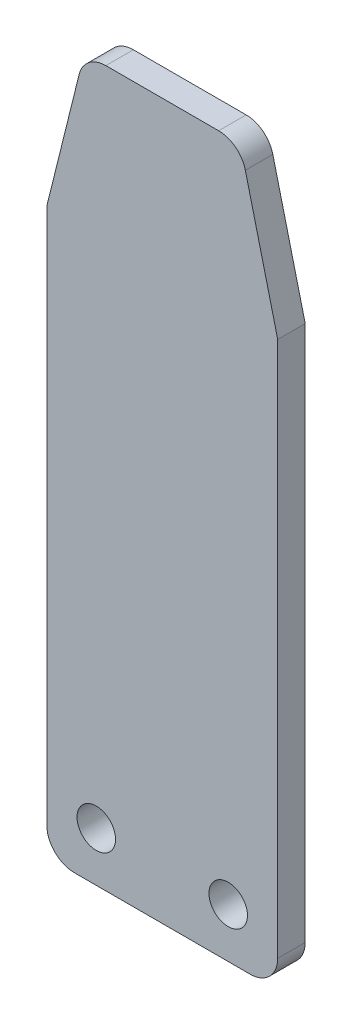
SolidWorks part; units mm, degrees
material "1.0116 (S235J2G3)"
ref_plane "Front Plane" through (0, 0, 0) normal (0, 0, 1) x (1, 0, 0)
ref_plane "Top Plane" through (0, 0, 0) normal (0, 1, 0) x (1, 0, 0)
ref_plane "Right Plane" through (0, 0, 0) normal (1, 0, 0) x (0, 0, -1)
sketch "Sketch1" plane through (0, 0, 0) normal (0, 0, 1) x (1, 0, 0)
  line L0 (-20.5177, 260) -> (20.5177, 260)
  line L1 (30.2228, 252.4108) -> (42, 205)
  line L2 (42, 205) -> (42, 10)
  line L3 (32, 0) -> (-32, 0)
  line L4 (0, 260) -> (0, 0) construction
  line L5 (-42, 205) -> (-42, 10)
  line L6 (-30.2228, 252.4108) -> (-42, 205)
  arc A0 (20.5177, 260) -> (30.2228, 252.4108) centre (20.5177, 250) cw
  circle A1 centre (24, 18) radius 7
  arc A2 (42, 10) -> (32, 0) centre (32, 10) cw
  circle A3 centre (-24, 18) radius 7
  arc A4 (-42, 10) -> (-32, 0) centre (-32, 10) ccw
  arc A5 (-20.5177, 260) -> (-30.2228, 252.4108) centre (-20.5177, 250) ccw
  point P15 (42, 0)
  point P19 (0, 0)
  dimension "D7" = 10
  dimension "D8" = 10
  dimension "D9" = 14
  dimension "D10" = 18
  dimension "D11" = 18
  dimension "D1" = 42
  dimension "D2" = 205
  dimension "D3" = 41.0354
  dimension "D4" = 260
  dimension "D6" = 0
extrude "Boss-Extrude1" add sketch "Sketch1" along normal blind 10
